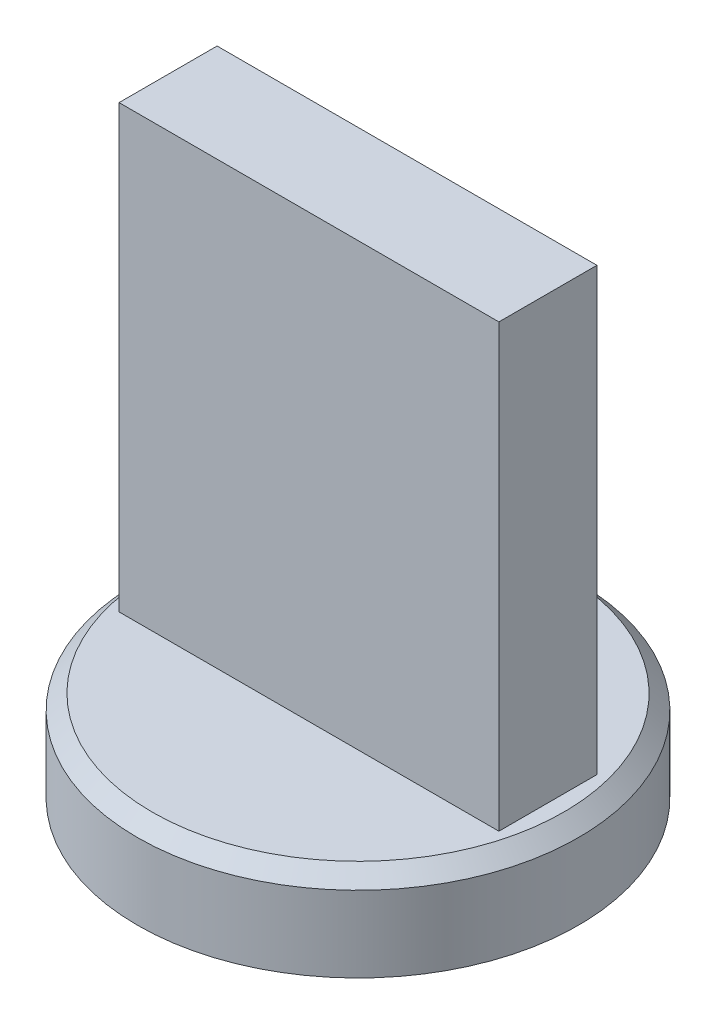
SolidWorks part; units mm, degrees
ref_plane "Front Plane" through (0, 0, 0) normal (0, 0, 1) x (1, 0, 0)
ref_plane "Top Plane" through (0, 0, 0) normal (0, 1, 0) x (1, 0, 0)
ref_plane "Right Plane" through (0, 0, 0) normal (1, 0, 0) x (0, 0, -1)
sketch "Sketch2" plane through (0, 0, 0) normal (0, 1, 0) x (1, 0, 0)
  circle A0 centre (0, 0) radius 90
  dimension "D1" = 180
extrude "Boss-Extrude1" add sketch "Sketch2" along normal blind 37
fillet "Chamfer1" radius 6 1 edges at (0, 37, 90) profile chamfer
sketch "Sketch3" plane through (0, 37, 0) normal (0, 1, 0) x (1, 0, 0)
  line L1 (-77.5, 20) -> (77.5, 20)
  line L2 (-77.5, 20) -> (-77.5, -20)
  line L3 (-77.5, -20) -> (77.5, -20)
  line L4 (77.5, 20) -> (77.5, -20)
  line L5 (-77.5, 20) -> (77.5, -20) construction
  line L6 (-77.5, -20) -> (77.5, 20) construction
  point P0 (0, 0)
  dimension "D1" = 155
  dimension "D2" = 40
extrude "Boss-Extrude2" add sketch "Sketch3" along normal blind 180
ref_plane "Plane5" through (0, 0, 30) normal (0, 0, 1) x (1, 0, 0)
sketch "Sketch30" plane through (0, 0, 0) normal (0, -1, 0) x (1, 0, 0)
  circle A0 centre (0, 0) radius 15
  dimension "D1" = 30
extrude "Cut-Extrude1" cut sketch "Sketch30" against normal blind 20
sketch "Sketch31" plane through (0, 0, -20) normal (0, 0, -1) x (-1, 0, 0)
  circle A0 centre (0, 197) radius 15
extrude "Cut-Extrude2" cut sketch "Sketch31" against normal blind 20
